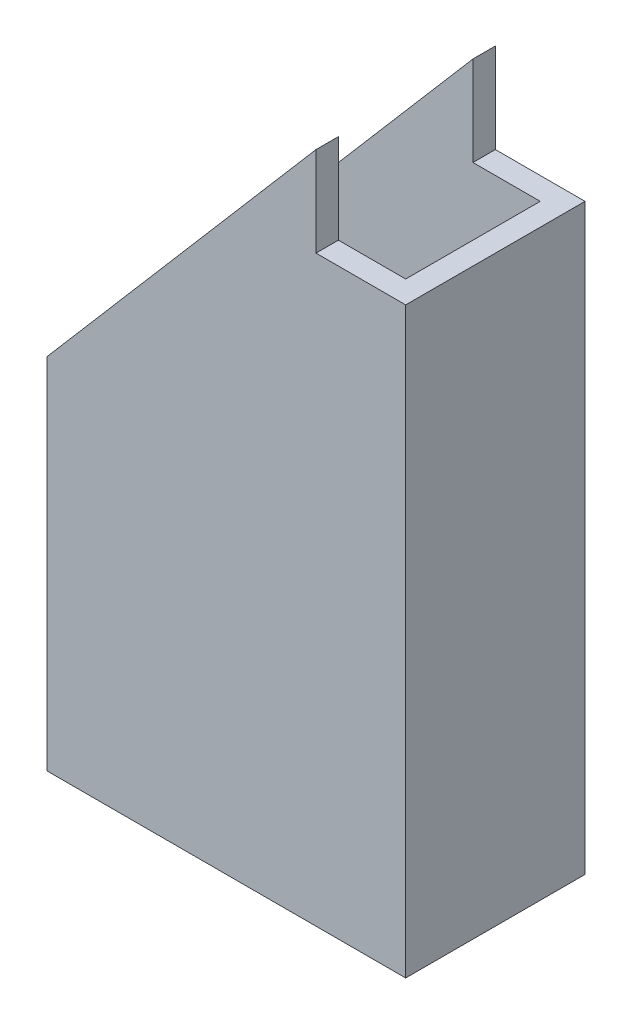
SolidWorks part; units mm, degrees
ref_plane "Front Plane" through (0, 0, 0) normal (0, 0, 1) x (1, 0, 0)
ref_plane "Top Plane" through (0, 0, 0) normal (0, 1, 0) x (1, 0, 0)
ref_plane "Right Plane" through (0, 0, 0) normal (1, 0, 0) x (0, 0, -1)
sketch "Sketch1" plane through (0, 0, 0) normal (0, 0, 1) x (1, 0, 0)
  line L0 (25.4, 3.175) -> (-25.4, 3.175) construction
  line L1 (-25.4, -47.625) -> (25.4, -47.625)
  line L2 (-25.4, -47.625) -> (-25.4, 3.175)
  line L4 (25.4, -47.625) -> (25.4, 34.925)
  line L7 (-25.4, 3.175) -> (12.7, 47.625)
  line L10 (12.7, 47.625) -> (12.7, 34.925)
  line L11 (12.7, 34.925) -> (25.4, 34.925)
  point P0 (0, 0)
  dimension "D1" = 95.25
  dimension "D2" = 50.8
  dimension "D3" = 50.8
  dimension "D4" = 12.7
  dimension "D5" = 12.7
extrude "Boss-Extrude1" add sketch "Sketch1" along normal mid plane 25.4
sketch "Sketch2" plane through (0, -47.625, 0) normal (0, -1, 0) x (1, 0, 0)
  line L8 (-22.225, -9.525) -> (22.225, -9.525)
  line L9 (22.225, -9.525) -> (22.225, 9.525)
  line L10 (22.225, 9.525) -> (-22.225, 9.525)
  line L11 (-22.225, 9.525) -> (-22.225, -9.525)
  line L12 (-22.225, -9.525) -> (22.225, -9.525)
  line L13 (22.225, -9.525) -> (22.225, 9.525)
  line L14 (22.225, 9.525) -> (-22.225, 9.525)
  line L15 (-22.225, 9.525) -> (-22.225, -9.525)
  dimension "D1" = 3.175
extrude "Cut-Extrude1" cut sketch "Sketch2" against normal through all
